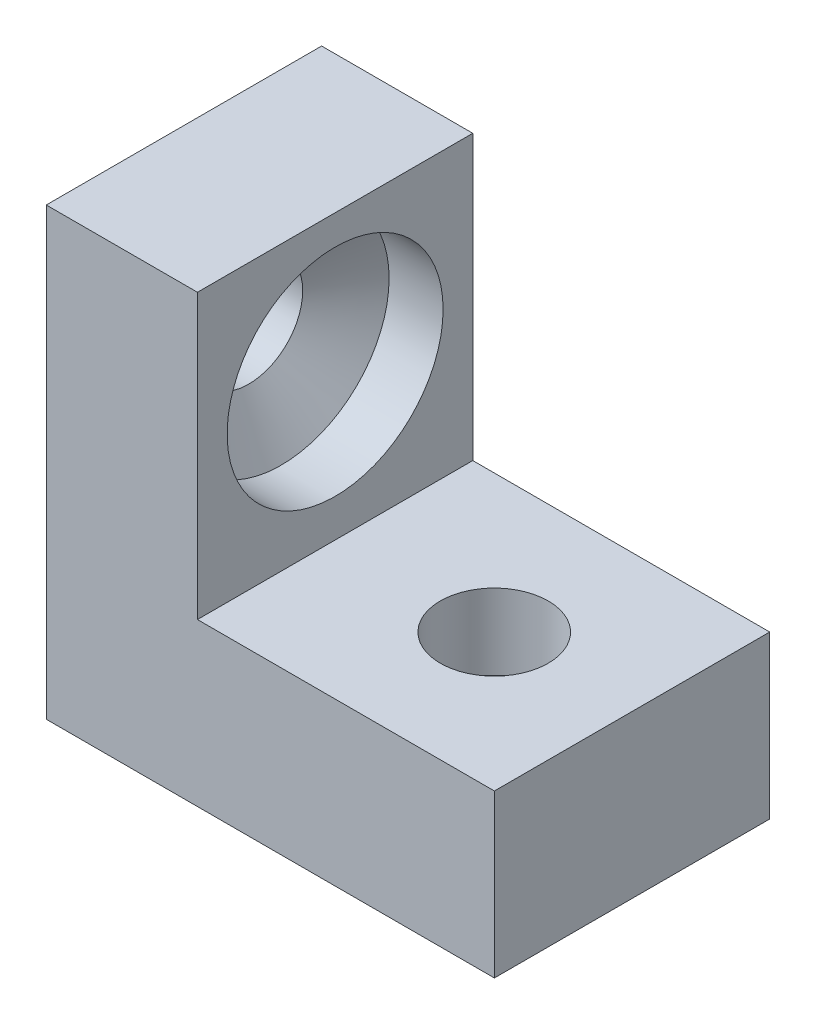
SolidWorks part; units mm, degrees
ref_plane "Plan de face" through (0, 0, 0) normal (0, 0, 1) x (1, 0, 0)
ref_plane "Plan de dessus" through (0, 0, 0) normal (0, 1, 0) x (1, 0, 0)
ref_plane "Plan de droite" through (0, 0, 0) normal (1, 0, 0) x (0, 0, -1)
sketch "Esquisse1" plane through (0, 0, 0) normal (0, 1, 0) x (1, 0, 0)
  line L0 (6.75, 2.55) -> (8.3, 2.55) construction
  line L1 (0, 0) -> (8.3, 0)
  line L2 (0, 0) -> (0, 5.1)
  line L3 (0, 5.1) -> (8.3, 5.1)
  line L4 (8.3, 0) -> (8.3, 5.1)
  line L5 (5.75, 3.55) -> (5.75, 5.1) construction
  line L6 (5.75, 1.55) -> (5.75, 0) construction
  circle A0 centre (5.75, 2.55) radius 1 construction
  dimension "D1" = 5.1
  dimension "D2" = 8.3
extrude "Boss.-Extru.1" add sketch "Esquisse1" along normal blind 3
sketch "Esquisse2" plane through (0, 3, 0) normal (0, 1, 0) x (1, 0, 0)
  line L0 (8.3, 5.1) -> (0, 5.1) construction
  line L1 (0, 0) -> (2.8, 0)
  line L2 (0, 0) -> (0, 5.1)
  line L3 (0, 5.1) -> (2.8, 5.1)
  line L4 (2.8, 0) -> (2.8, 5.1)
  dimension "D1" = 2.8
extrude "Boss.-Extru.2" add sketch "Esquisse2" along normal blind 5.25
sketch "Esquisse3" plane through (2.8, 0, 0) normal (1, 0, 0) x (0, 0, -1)
  line L0 (2.55, 6.7) -> (2.55, 8.25) construction
  line L1 (0, 8.25) -> (5.1, 8.25) construction
  line L2 (1.55, 5.7) -> (0, 5.7) construction
  line L3 (0, 8.25) -> (0, 3) construction
  line L4 (3.55, 5.7) -> (5.1, 5.7) construction
  line L5 (5.1, 8.25) -> (5.1, 3) construction
  circle A0 centre (2.55, 5.7) radius 1 construction
  dimension "D1" = 2
hole_wizard "Perçage1" positions "Esquisse5" profile "Esquisse6" legacy end condition through all
sketch "Esquisse5" plane through (2.8, 0, 0) normal (1, 0, 0) x (0, 0, -1)
  point P0 (2.55, 5.7)
sketch "Esquisse6" plane through (2.8, 5.7, -2.55) normal (0, 1, 0) x (0, 0, -1)
  line L0 (0, 0) -> (0, 3.4009)
  line L1 (0, 3.4009) -> (1, 2.8)
  line L2 (1, 2.8) -> (1, 1.6009)
  line L3 (1, 1.6009) -> (2, 1)
  line L4 (2, 1) -> (2, 0)
  line L5 (2, 0) -> (0, 0)
  line L6 (0, -6.13) -> (0, 109.2824) construction
  line L7 (-1, 1.6009) -> (-2, 1) construction
  line L8 (0, 3.4009) -> (-1, 2.8) construction
  dimension "Diamètre" = 2
  dimension "Profondeur" = 2.8
  dimension "Diamètre contre-pointe" = 4
  dimension "Profondeur contre-pointe" = 1
  dimension "Angle" = 118
  dimension "Angle contre-pointe" = 118
hole_wizard "Perçage2" positions "Esquisse8" profile "Esquisse9" legacy
sketch "Esquisse8" plane through (0, 0, 0) normal (0, -1, 0) x (-1, 0, 0)
  point P0 (-5.7502, 2.5473)
sketch "Esquisse9" plane through (5.7502, 0, -2.5473) normal (1, 0, 0) x (0, 0, -1)
  line L0 (0, 0) -> (0, 10.6009)
  line L1 (0, 10.6009) -> (1, 10)
  line L2 (1, 10) -> (1, 1.6009)
  line L3 (1, 1.6009) -> (2, 1)
  line L4 (2, 1) -> (2, 0)
  line L5 (2, 0) -> (0, 0)
  line L6 (0, -6.13) -> (0, 109.2824) construction
  line L7 (-1, 1.6009) -> (-2, 1) construction
  line L8 (0, 10.6009) -> (-1, 10) construction
  dimension "Diamètre" = 2
  dimension "Profondeur" = 10
  dimension "Diamètre contre-pointe" = 4
  dimension "Profondeur contre-pointe" = 1
  dimension "Angle" = 118
  dimension "Angle contre-pointe" = 118
